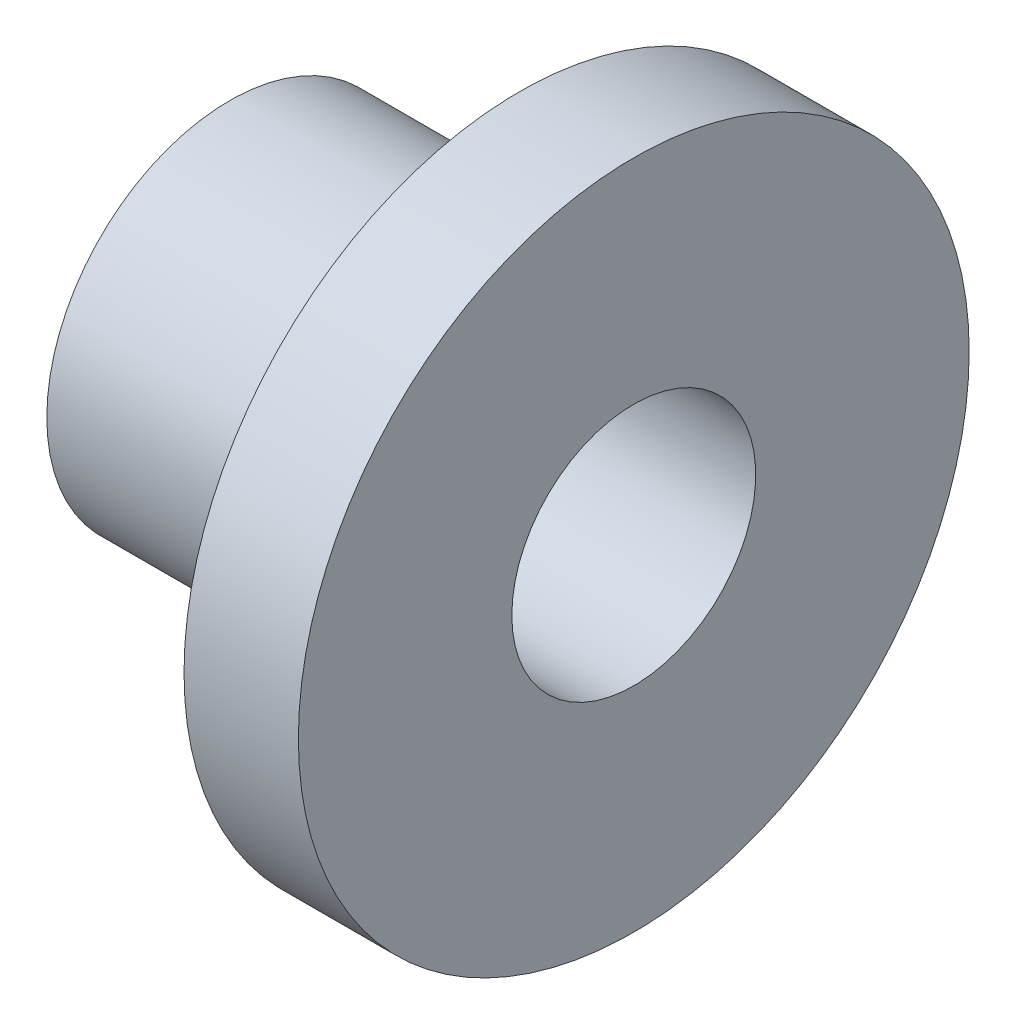
SolidWorks part; units mm, degrees
ref_plane "前视基准面" through (0, 0, 0) normal (0, 0, 1) x (1, 0, 0)
ref_plane "上视基准面" through (0, 0, 0) normal (0, 1, 0) x (1, 0, 0)
ref_plane "右视基准面" through (0, 0, 0) normal (1, 0, 0) x (0, 0, -1)
other "Configuration Table"
sketch "草图1" plane through (0, 0, 0) normal (0, 0, 1) x (1, 0, 0)
  line L0 (0, 0) -> (9.5, 0)
  line L1 (5.3, 1.6) -> (5.3, 4.4)
  line L2 (5.3, 4.4) -> (3.8, 4.4)
  line L3 (0, 1.6) -> (0, 2.4)
  line L4 (0, 2.4) -> (3.8, 2.4)
  line L5 (3.8, 2.4) -> (3.8, 4.4)
  line L6 (0, 1.6) -> (5.3, 1.6)
  dimension "D1" = 1.5
  dimension "D2" = 2.4
  dimension "D3" = 3.8
  dimension "D4" = 2
  dimension "D5" = 1.6
revolve "旋转1" add sketch "草图1" angle 360 about L0
